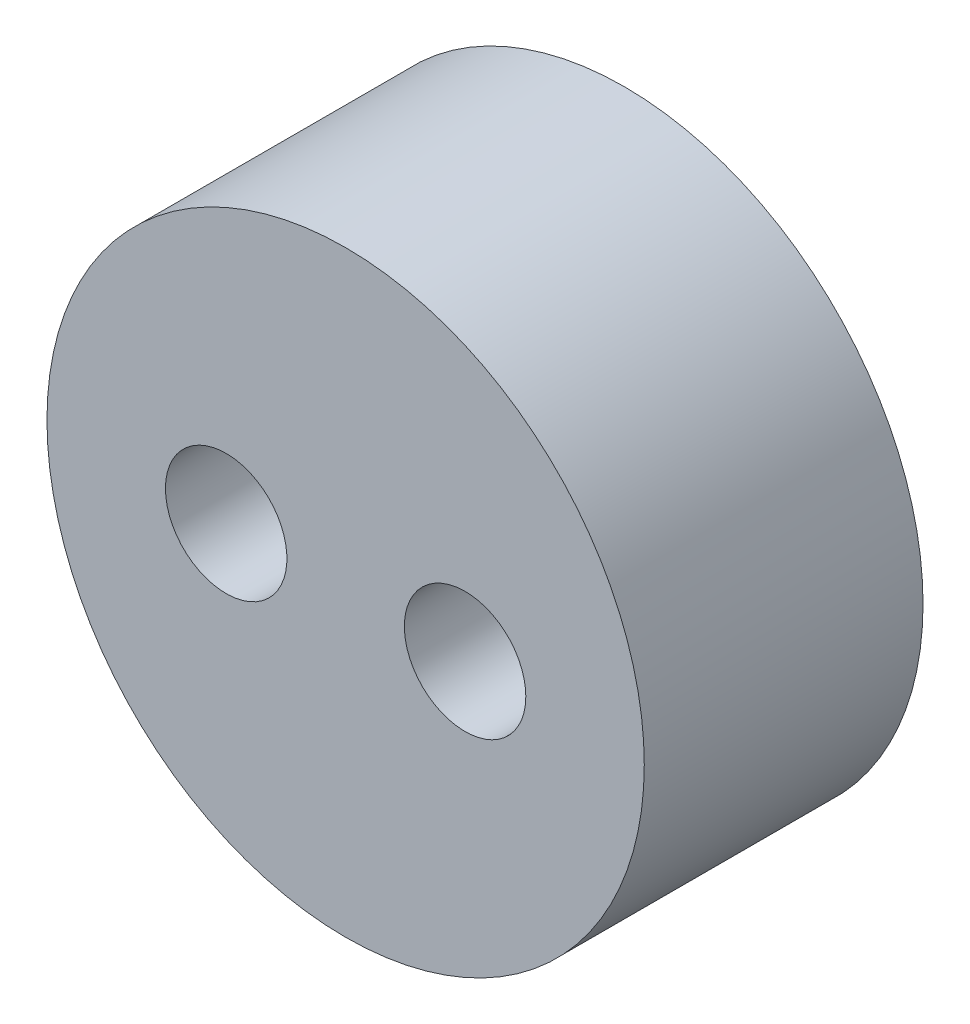
SolidWorks part; units mm, degrees
ref_plane "Front Plane" through (0, 0, 0) normal (0, 0, 1) x (1, 0, 0)
ref_plane "Top Plane" through (0, 0, 0) normal (0, 1, 0) x (1, 0, 0)
ref_plane "Right Plane" through (0, 0, 0) normal (1, 0, 0) x (0, 0, -1)
sketch "Sketch1" plane through (0, 0, 0) normal (0, 0, 1) x (1, 0, 0)
  circle A0 centre (0, 0) radius 7.5
  dimension "D1" = 15
extrude "Boss-Extrude1" add sketch "Sketch1" along normal blind 7
sketch "Sketch2" plane through (0, 0, 7) normal (0, 0, 1) x (1, 0, 0)
  line L0 (-8.381, 0) -> (9.7311, 0) construction
  line L1 (0, 7.7849) -> (0, -8.0479) construction
  circle A0 centre (3, 0) radius 1.525
  circle A1 centre (-3, 0) radius 1.525
  dimension "D1" = 3.05
  dimension "D2" = 3
extrude "Cut-Extrude1" cut sketch "Sketch2" against normal through all contours A1 | A0
